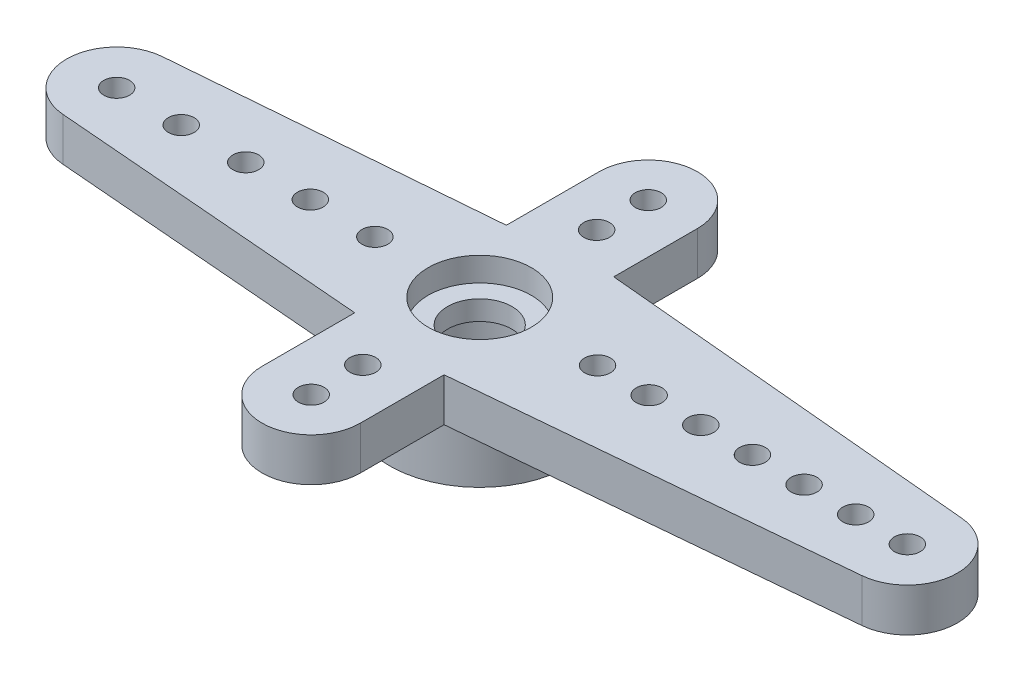
SolidWorks part; units mm, degrees
ref_plane "Front Plane" through (0, 0, 0) normal (0, 0, 1) x (1, 0, 0)
ref_plane "Top Plane" through (0, 0, 0) normal (0, 1, 0) x (1, 0, 0)
ref_plane "Right Plane" through (0, 0, 0) normal (1, 0, 0) x (0, 0, -1)
sketch "Sketch1" plane through (0, 0, 0) normal (0, 0, 1) x (1, 0, 0)
  line L0 (2.25, 0) -> (1.25, 0)
  line L1 (1.25, 0) -> (1.25, 0.76)
  line L2 (1.25, 0.76) -> (2, 0.76)
  line L3 (2, 0.76) -> (2, 1.69)
  line L4 (2, 1.69) -> (3.5, 1.69)
  line L5 (3.5, 1.69) -> (3.5, -2.21)
  line L6 (3.5, -2.21) -> (2.25, -2.21)
  line L7 (2.25, -2.21) -> (2.25, 0)
  line L8 (0, 0) -> (0, 1.69) construction
  line L9 (0, 0) -> (0, -2.21) construction
  point P2 (1.267, 0)
  point P7 (0, 0)
  point P10 (1.6619, 0)
  point P11 (2.2458, 2.3634)
  point P12 (2.2458, 0)
  point P16 (1.3013, 0)
  point P18 (1.8852, 0)
  point P19 (2.5721, 0)
  dimension "D1" = 7
  dimension "D2" = 3.9
  dimension "D3" = 0.93
  dimension "D4" = 1.5
  dimension "D5" = 2.21
  dimension "D6" = 2.5
  dimension "D7" = 4.5
revolve "Revolve1" add sketch "Sketch1" angle 360 about L9
sketch "Sketch2" plane through (0, 1.69, 0) normal (0, 1, 0) x (1, 0, 0)
  line L0 (0, 6.5278) -> (0, -6.5278) construction
  line L1 (1.905, 6.5278) -> (1.905, -6.5278) construction
  line L2 (-1.905, 6.5278) -> (-1.905, -6.5278) construction
  line L3 (-1.905, 6.5278) -> (-1.905, 2.9361)
  line L4 (1.905, 6.5278) -> (1.905, 2.9361)
  arc A0 (1.905, 6.5278) -> (-1.905, 6.5278) centre (0, 6.5278) ccw construction
  arc A1 (-1.905, -6.5278) -> (1.905, -6.5278) centre (0, -6.5278) ccw construction
  arc A2 (-1.905, 6.5278) -> (1.905, 6.5278) centre (0, 6.5278) cw
  circle A3 centre (0, 0) radius 3.5 construction
  arc A4 (-1.905, 2.9361) -> (1.905, 2.9361) centre (0, 0) cw
  circle A5 centre (0, 6.5278) radius 0.5
  circle A6 centre (0, 4.5278) radius 0.5
  point P3 (0, 0)
  point P8 (0, -8.4328)
  point P9 (0, 8.4328)
  dimension "D4" = 1
  dimension "D1" = 3.81
  dimension "D2" = 16.8656
  dimension "D3" = 2
extrude "Boss-Extrude1" add sketch "Sketch2" against normal blind 1.675
pattern_circular "CirPattern1" count 2 over 360 about axis through (0, 0, 0) along (0, 1, 0) of "Boss-Extrude1"
sketch "Sketch3" plane through (0, 0.015, 0) normal (0, -1, 0) x (1, 0, 0)
  line L0 (0.927, -3.375) -> (16.7389, -1.9295)
  line L1 (0.927, 3.375) -> (16.7389, 1.9295)
  arc A0 (0.927, 3.375) -> (0.927, -3.375) centre (0, 0) cw
  circle A1 centre (0, 0) radius 3.5 construction
  arc A2 (16.7389, 1.9295) -> (16.7389, -1.9295) centre (16.5625, 0) cw
  circle A3 centre (16.5625, 0) radius 0.5
  circle A4 centre (14.5625, 0) radius 0.5
  circle A5 centre (12.5625, 0) radius 0.5
  circle A6 centre (10.5625, 0) radius 0.5
  circle A7 centre (8.5625, 0) radius 0.5
  circle A8 centre (6.5625, 0) radius 0.5
  circle A9 centre (4.5625, 0) radius 0.5
  point P8 (18.5, 0)
  point P10 (3.5, 0)
  point P11 (8.355, 0)
  point P25 (5.2084, 0)
  dimension "D2" = 1.9375
  dimension "D4" = 1
  dimension "D1" = 15
  dimension "D3" = 6.75
  dimension "D6" = 12
  dimension "D5" = 7
extrude "Boss-Extrude2" add sketch "Sketch3" against normal up to surface (1.675 mm away)
sketch "Sketch4" plane through (0, 0.015, 0) normal (0, -1, 0) x (1, 0, 0)
  line L0 (-1.905, 2.9361) -> (-14.2201, 1.9311)
  line L1 (-14.2201, -1.9311) -> (-1.905, -2.9361)
  arc A0 (-14.2201, 1.9311) -> (-14.2201, -1.9311) centre (-14.0625, 0) ccw
  circle A1 centre (-14.0625, 0) radius 0.5
  circle A2 centre (-11.5625, 0) radius 0.5
  circle A3 centre (-9.0625, 0) radius 0.5
  circle A4 centre (-6.5625, 0) radius 0.5
  circle A5 centre (-4.0625, 0) radius 0.5
  circle A6 centre (4.5625, 0) radius 0.5 construction
  arc A7 (-1.905, 2.9361) -> (-1.905, -2.9361) centre (0, 0) ccw
  arc A8 (16.7389, -1.9295) -> (16.7389, 1.9295) centre (16.5625, 0) ccw construction
  point P5 (-16, 0)
  point P21 (-3.5, 0)
  dimension "D2" = 10
  dimension "D3" = 12.5
  dimension "D1" = 5
extrude "Boss-Extrude3" add sketch "Sketch4" against normal up to surface (1.675 mm away)
